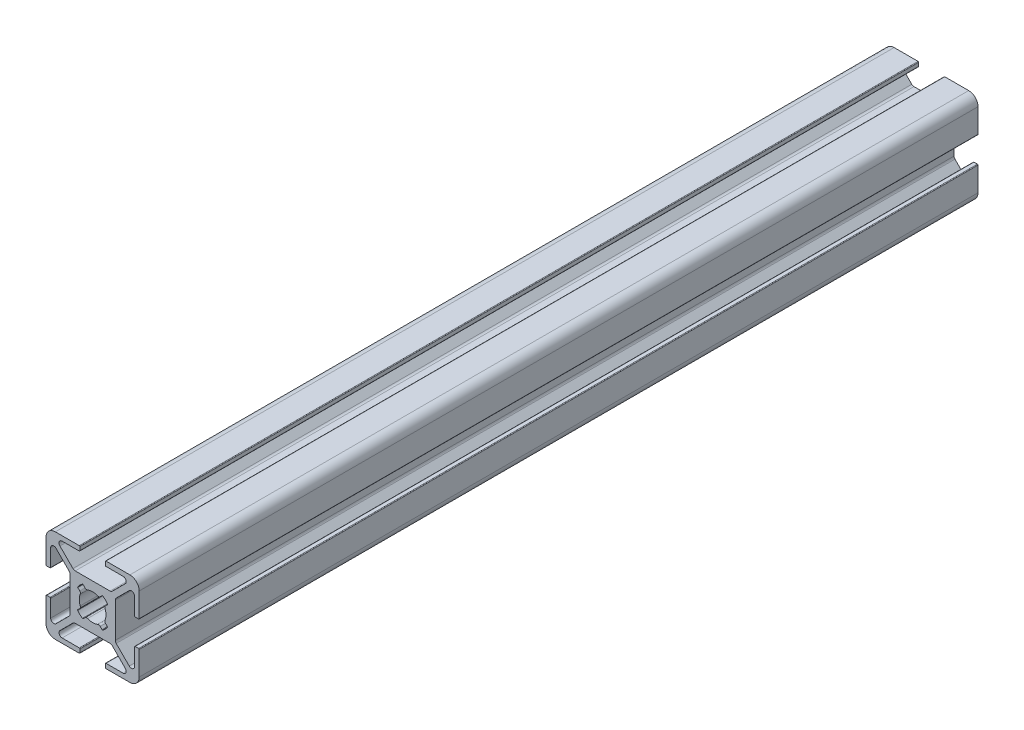
SolidWorks part; units mm, degrees
material "6061 Alloy"
ref_plane "Front Plane" through (0, 0, 0) normal (0, 0, 1) x (1, 0, 0)
ref_plane "Top Plane" through (0, 0, 0) normal (0, 1, 0) x (1, 0, 0)
ref_plane "Right Plane" through (0, 0, 0) normal (1, 0, 0) x (0, 0, -1)
sketch "Sketch1" plane through (0, 0, 0) normal (0, 0, 1) x (1, 0, 0)
  line L0 (0, 0) -> (-24.914, 24.914) construction
  line L1 (-12, 15) -> (-4.3, 15)
  line L2 (15, 12) -> (15, 4.3)
  line L3 (-3.0476, 4.7447) -> (-2.4454, 4.1425)
  line L4 (-4.7447, 3.0476) -> (-4.1425, 2.4454)
  line L5 (0, 23.6023) -> (0, -23.6023) construction
  line L6 (-23.6023, 0) -> (23.6023, 0) construction
  line L7 (-4.1, 14.8) -> (-4.1, 13.7)
  line L8 (-5.613, 7.3) -> (5.613, 7.3)
  line L9 (-7.3, 5.613) -> (-7.3, -5.613)
  line L10 (-5.613, -7.3) -> (5.613, -7.3)
  line L11 (7.3, 5.613) -> (7.3, -5.613)
  line L12 (-4.3, 13.5) -> (-9.813, 13.5)
  line L13 (-10.5201, 11.7929) -> (-6.3201, 7.5929)
  line L14 (-11.7929, 10.5201) -> (-7.5929, 6.3201)
  line L15 (-13.5, 4.3) -> (-13.5, 9.813)
  line L16 (-14.8, 4.1) -> (-13.7, 4.1)
  line L17 (-15, 12) -> (-15, 4.3)
  line L18 (14.8, 4.1) -> (13.7, 4.1)
  line L19 (13.5, 4.3) -> (13.5, 9.813)
  line L20 (11.7929, 10.5201) -> (7.5929, 6.3201)
  line L21 (10.5201, 11.7929) -> (6.3201, 7.5929)
  line L22 (4.3, 13.5) -> (9.813, 13.5)
  line L23 (4.1, 14.8) -> (4.1, 13.7)
  line L24 (12, 15) -> (4.3, 15)
  line L25 (12, -15) -> (4.3, -15)
  line L26 (4.1, -14.8) -> (4.1, -13.7)
  line L27 (4.3, -13.5) -> (9.813, -13.5)
  line L28 (10.5201, -11.7929) -> (6.3201, -7.5929)
  line L29 (11.7929, -10.5201) -> (7.5929, -6.3201)
  line L30 (13.5, -4.3) -> (13.5, -9.813)
  line L31 (14.8, -4.1) -> (13.7, -4.1)
  line L32 (-15, -12) -> (-15, -4.3)
  line L33 (-14.8, -4.1) -> (-13.7, -4.1)
  line L34 (-13.5, -4.3) -> (-13.5, -9.813)
  line L35 (-11.7929, -10.5201) -> (-7.5929, -6.3201)
  line L36 (-10.5201, -11.7929) -> (-6.3201, -7.5929)
  line L37 (-4.3, -13.5) -> (-9.813, -13.5)
  line L38 (4.7447, 3.0476) -> (4.1425, 2.4454)
  line L39 (-4.1, -14.8) -> (-4.1, -13.7)
  line L40 (15, -12) -> (15, -4.3)
  line L41 (-12, -15) -> (-4.3, -15)
  line L42 (0, 0) -> (-24.914, -24.914) construction
  line L43 (3.0476, 4.7447) -> (2.4454, 4.1425)
  line L44 (3.0476, -4.7447) -> (2.4454, -4.1425)
  line L45 (4.7447, -3.0476) -> (4.1425, -2.4454)
  line L46 (-4.7447, -3.0476) -> (-4.1425, -2.4454)
  line L47 (-3.0476, -4.7447) -> (-2.4454, -4.1425)
  circle A0 centre (0, 0) radius 5.8 construction
  arc A1 (-4.1, 14.8) -> (-4.3, 15) centre (-4.3, 14.8) ccw
  arc A2 (-4.1, 13.7) -> (-4.3, 13.5) centre (-4.3, 13.7) cw
  arc A3 (-10.5201, 11.7929) -> (-9.813, 13.5) centre (-9.813, 12.5) cw
  arc A4 (-5.613, 7.3) -> (-6.3201, 7.5929) centre (-5.613, 8.3) cw
  arc A5 (-15, 12) -> (-12, 15) centre (-12, 12) cw
  arc A6 (-7.3, 5.613) -> (-7.5929, 6.3201) centre (-8.3, 5.613) ccw
  arc A7 (-11.7929, 10.5201) -> (-13.5, 9.813) centre (-12.5, 9.813) ccw
  arc A8 (-13.7, 4.1) -> (-13.5, 4.3) centre (-13.7, 4.3) ccw
  arc A9 (-14.8, 4.1) -> (-15, 4.3) centre (-14.8, 4.3) cw
  arc A10 (14.8, 4.1) -> (15, 4.3) centre (14.8, 4.3) ccw
  arc A11 (13.7, 4.1) -> (13.5, 4.3) centre (13.7, 4.3) cw
  arc A12 (11.7929, 10.5201) -> (13.5, 9.813) centre (12.5, 9.813) cw
  arc A13 (7.3, 5.613) -> (7.5929, 6.3201) centre (8.3, 5.613) cw
  arc A14 (15, 12) -> (12, 15) centre (12, 12) ccw
  arc A15 (5.613, 7.3) -> (6.3201, 7.5929) centre (5.613, 8.3) ccw
  arc A16 (10.5201, 11.7929) -> (9.813, 13.5) centre (9.813, 12.5) ccw
  arc A17 (4.1, 13.7) -> (4.3, 13.5) centre (4.3, 13.7) ccw
  arc A18 (4.1, 14.8) -> (4.3, 15) centre (4.3, 14.8) cw
  arc A19 (4.1, -14.8) -> (4.3, -15) centre (4.3, -14.8) ccw
  arc A20 (4.1, -13.7) -> (4.3, -13.5) centre (4.3, -13.7) cw
  arc A21 (10.5201, -11.7929) -> (9.813, -13.5) centre (9.813, -12.5) cw
  arc A22 (5.613, -7.3) -> (6.3201, -7.5929) centre (5.613, -8.3) cw
  arc A23 (15, -12) -> (12, -15) centre (12, -12) cw
  arc A24 (7.3, -5.613) -> (7.5929, -6.3201) centre (8.3, -5.613) ccw
  arc A25 (11.7929, -10.5201) -> (13.5, -9.813) centre (12.5, -9.813) ccw
  arc A26 (13.7, -4.1) -> (13.5, -4.3) centre (13.7, -4.3) ccw
  arc A27 (14.8, -4.1) -> (15, -4.3) centre (14.8, -4.3) cw
  arc A28 (-14.8, -4.1) -> (-15, -4.3) centre (-14.8, -4.3) ccw
  arc A29 (-13.7, -4.1) -> (-13.5, -4.3) centre (-13.7, -4.3) cw
  arc A30 (-11.7929, -10.5201) -> (-13.5, -9.813) centre (-12.5, -9.813) cw
  arc A31 (-7.3, -5.613) -> (-7.5929, -6.3201) centre (-8.3, -5.613) cw
  arc A32 (-15, -12) -> (-12, -15) centre (-12, -12) ccw
  arc A33 (-5.613, -7.3) -> (-6.3201, -7.5929) centre (-5.613, -8.3) ccw
  arc A34 (-10.5201, -11.7929) -> (-9.813, -13.5) centre (-9.813, -12.5) ccw
  arc A35 (-4.1, -13.7) -> (-4.3, -13.5) centre (-4.3, -13.7) ccw
  arc A36 (-4.1, -14.8) -> (-4.3, -15) centre (-4.3, -14.8) cw
  arc A37 (-3.9788, 1.6307) -> (-3.9788, -1.6307) centre (0, 0) ccw
  arc A38 (-3.3029, 4.7677) -> (-4.7677, 3.3029) centre (0, 0) ccw
  arc A39 (1.6307, 3.9788) -> (-1.6307, 3.9788) centre (0, 0) ccw
  arc A40 (-3.9788, 1.6307) -> (-4.1425, 2.4454) centre (-4.6728, 1.9151) ccw
  arc A41 (-1.6307, 3.9788) -> (-2.4454, 4.1425) centre (-1.9151, 4.6728) cw
  arc A42 (-3.3029, 4.7677) -> (-3.0476, 4.7447) centre (-3.189, 4.6033) cw
  arc A43 (-4.7447, 3.0476) -> (-4.7677, 3.3029) centre (-4.6033, 3.189) cw
  arc A44 (4.7447, 3.0476) -> (4.7677, 3.3029) centre (4.6033, 3.189) ccw
  arc A45 (3.3029, 4.7677) -> (3.0476, 4.7447) centre (3.189, 4.6033) ccw
  arc A46 (1.6307, 3.9788) -> (2.4454, 4.1425) centre (1.9151, 4.6728) ccw
  arc A47 (3.9788, 1.6307) -> (4.1425, 2.4454) centre (4.6728, 1.9151) cw
  arc A48 (3.3029, 4.7677) -> (4.7677, 3.3029) centre (0, 0) cw
  arc A49 (3.9788, 1.6307) -> (3.9788, -1.6307) centre (0, 0) cw
  arc A50 (3.3029, -4.7677) -> (4.7677, -3.3029) centre (0, 0) ccw
  arc A51 (3.9788, -1.6307) -> (4.1425, -2.4454) centre (4.6728, -1.9151) ccw
  arc A52 (1.6307, -3.9788) -> (2.4454, -4.1425) centre (1.9151, -4.6728) cw
  arc A53 (3.3029, -4.7677) -> (3.0476, -4.7447) centre (3.189, -4.6033) cw
  arc A54 (4.7447, -3.0476) -> (4.7677, -3.3029) centre (4.6033, -3.189) cw
  arc A55 (-4.7447, -3.0476) -> (-4.7677, -3.3029) centre (-4.6033, -3.189) ccw
  arc A56 (-3.3029, -4.7677) -> (-3.0476, -4.7447) centre (-3.189, -4.6033) ccw
  arc A57 (-1.6307, -3.9788) -> (-2.4454, -4.1425) centre (-1.9151, -4.6728) ccw
  arc A58 (-3.9788, -1.6307) -> (-4.1425, -2.4454) centre (-4.6728, -1.9151) cw
  arc A59 (1.6307, -3.9788) -> (-1.6307, -3.9788) centre (0, 0) cw
  arc A60 (-3.3029, -4.7677) -> (-4.7677, -3.3029) centre (0, 0) cw
  point P13 (3.164, -4.861)
  point P130 (-3.164, 4.861)
  point P133 (-4.861, 3.164)
  point P146 (4.861, 3.164)
  point P147 (3.164, 4.861)
  point P171 (4.861, -3.164)
  point P172 (-4.861, -3.164)
  point P173 (-3.164, -4.861)
  dimension "D1" = 11.6
  dimension "D2" = 45
  dimension "D7" = 0.2
  dimension "D8" = 1
  dimension "D9" = 3
  dimension "D12" = 8.6
  dimension "D13" = 0.75
  dimension "D14" = 0.2
  dimension "D3" = 30
  dimension "D4" = 7.7
  dimension "D5" = 1.8
  dimension "D6" = 1.5
  dimension "D10" = 2.4
  dimension "D11" = 8.2
extrude "Extrude1" add sketch "Sketch1" along normal blind 270
